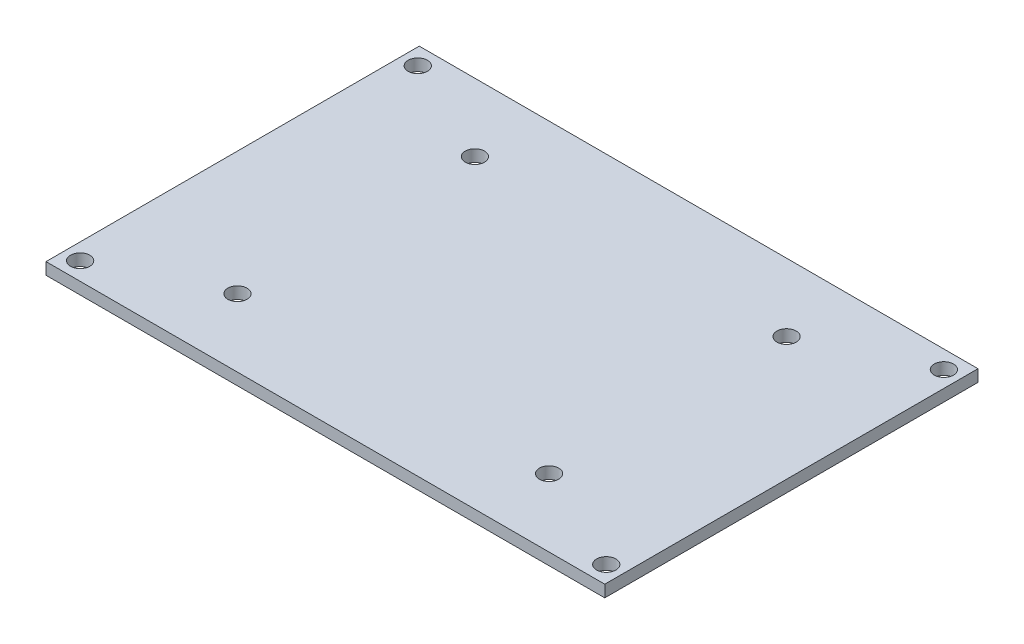
SolidWorks part; units mm, degrees
material "Placa de circuito impreso"
ref_plane "Alzado" through (0, 0, 0) normal (0, 0, 1) x (1, 0, 0)
ref_plane "Planta" through (0, 0, 0) normal (0, 1, 0) x (1, 0, 0)
ref_plane "Vista lateral" through (0, 0, 0) normal (1, 0, 0) x (0, 0, -1)
sketch "Croquis7" plane through (0, 0, 0) normal (0, 1, 0) x (1, 0, 0)
  line L1 (-37.65, 25.15) -> (37.65, 25.15)
  line L2 (-37.65, 25.15) -> (-37.65, -25.15)
  line L3 (-37.65, -25.15) -> (37.65, -25.15)
  line L4 (37.65, 25.15) -> (37.65, -25.15)
  line L5 (-37.65, 25.15) -> (37.65, -25.15) construction
  line L6 (-37.65, -25.15) -> (37.65, 25.15) construction
  point P0 (0, 0)
  dimension "D1" = 75.3
  dimension "D2" = 50.3
extrude "Saliente-Extruir1" add sketch "Croquis7" along normal blind 1.6
hole_wizard "Taladro de margen para M23" positions "Croquis15" profile "Croquis16" hole size "M2" standard "DIN" end condition through all
sketch "Croquis15" plane through (0, 1.6, 0) normal (0, 1, 0) x (1, 0, 0)
  line L0 (-35.45, 22.75) -> (35.45, 22.75) construction
  line L1 (35.45, 22.75) -> (35.45, -22.75) construction
  line L2 (35.45, -22.75) -> (-35.45, -22.75) construction
  line L3 (-35.45, -22.75) -> (-35.45, 22.75) construction
  line L5 (37.65, 25.15) -> (-37.65, 25.15) construction
  line L6 (-37.65, 25.15) -> (-37.65, -25.15) construction
  line L7 (37.65, -25.15) -> (37.65, 25.15) construction
  line L8 (-37.65, -25.15) -> (37.65, -25.15) construction
  point P0 (-35.45, 22.75)
  point P2 (35.45, 22.75)
  point P4 (35.45, -22.75)
  point P6 (-35.45, -22.75)
  dimension "D1" = 2.4
  dimension "D2" = 2.2
  dimension "D3" = 2.2
  dimension "D4" = 2.4
sketch "Croquis16" plane through (-35.45, 1.6, -22.75) normal (1, 0, 0) x (0, 0, 1)
  line L0 (0, 0) -> (0, 1.6)
  line L1 (0, 1.6) -> (1.3, 1.6)
  line L2 (1.3, 1.6) -> (1.3, 0)
  line L5 (1.3, 0) -> (0, 0)
  line L11 (0, -6.35) -> (0, 107.95) construction
  dimension "Diámetro de taladro hasta el siguiente" = 2.6
  dimension "Profundidad de taladro hasta el siguiente" = 1.6
hole_wizard "Taladro de margen para M24" positions "Croquis17" profile "Croquis18" hole size "M2" standard "DIN" end condition through all
sketch "Croquis17" plane through (0, 1.6, 0) normal (0, 1, 0) x (1, 0, 0)
  line L0 (-21, 16) -> (21, 16) construction
  line L1 (21, 16) -> (21, -16) construction
  line L2 (21, -16) -> (-21, -16) construction
  line L3 (-21, -16) -> (-21, 16) construction
  line L5 (-37.65, -25.15) -> (37.65, -25.15) construction
  line L6 (-37.65, 25.15) -> (-37.65, -25.15) construction
  point P0 (-21, 16)
  point P2 (21, 16)
  point P4 (21, -16)
  point P6 (-21, -16)
  dimension "D1" = 42
  dimension "D2" = 32
  dimension "D3" = 42
  dimension "D4" = 9.15
  dimension "D5" = 16.65
sketch "Croquis18" plane through (-21, 1.6, -16) normal (1, 0, 0) x (0, 0, 1)
  line L0 (0, 0) -> (0, 1.6)
  line L1 (0, 1.6) -> (1.3, 1.6)
  line L2 (1.3, 1.6) -> (1.3, 0)
  line L5 (1.3, 0) -> (0, 0)
  line L11 (0, -6.35) -> (0, 107.95) construction
  dimension "Diámetro de taladro hasta el siguiente" = 2.6
  dimension "Profundidad de taladro hasta el siguiente" = 1.6
